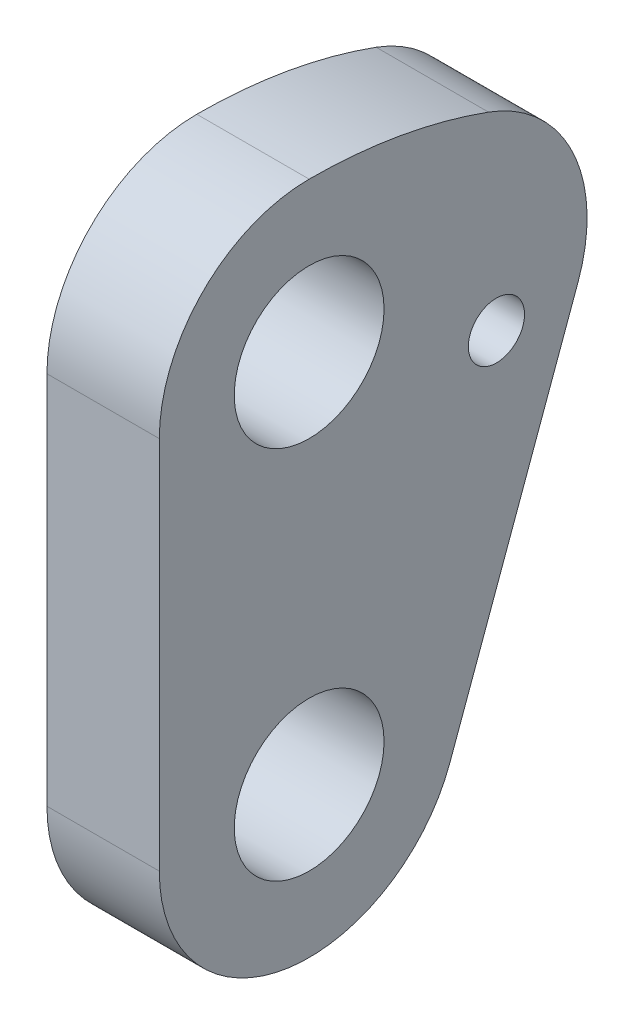
SolidWorks part; units mm, degrees
material "Plain Carbon Steel"
ref_plane "Front Plane" through (0, 0, 0) normal (0, 0, 1) x (1, 0, 0)
ref_plane "Top Plane" through (0, 0, 0) normal (0, 1, 0) x (1, 0, 0)
ref_plane "Right Plane" through (0, 0, 0) normal (1, 0, 0) x (0, 0, -1)
sketch "Sketch1" plane through (0, 0, 0) normal (1, 0, 0) x (0, 0, -1)
  line L0 (0, 0) -> (0, 14.2707) construction
  line L1 (0, 0) -> (5.2246, 14.3545) construction
  line L2 (-4, 10) -> (-4, 0)
  line L3 (3.7588, -1.3681) -> (7.179, 8.0288)
  circle A0 centre (0, 0) radius 2
  circle A1 centre (0, 10) radius 2
  arc A2 (-4, 0) -> (3.7588, -1.3681) centre (0, 0) ccw
  arc A3 (7.179, 8.0288) -> (4.7883, 13.1557) centre (3.4202, 9.3969) ccw
  arc A5 (0, 14) -> (4.7883, 13.1557) centre (0, 0) cw
  arc A6 (0, 14) -> (-4, 10) centre (0, 10) ccw
  dimension "D1" = 4
  dimension "D2" = 4
  dimension "D5" = 8
  dimension "D3" = 10
  dimension "D4" = 20
  dimension "D8" = 10
extrude "Boss-Extrude1" add sketch "Sketch1" along normal blind 3
sketch "Sketch2" plane through (3, 0, 0) normal (1, 0, 0) x (0, 0, -1)
  circle A0 centre (5, 8) radius 0.75
  dimension "D1" = 1.5
  dimension "D2" = 8
  dimension "D3" = 5
extrude "Cut-Extrude1" cut sketch "Sketch2" against normal through all
